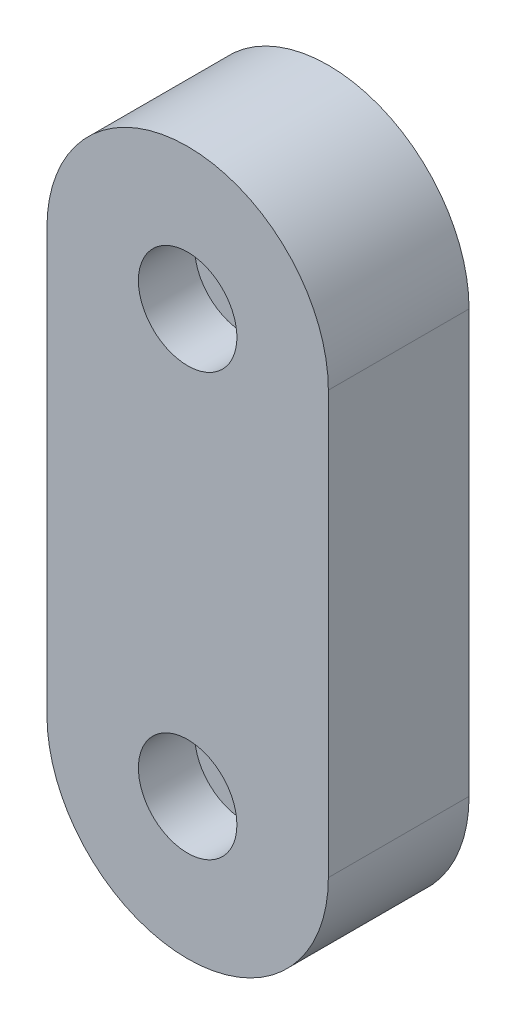
SolidWorks part; units mm, degrees
ref_plane "Front Plane" through (0, 0, 0) normal (0, 0, 1) x (1, 0, 0)
ref_plane "Top Plane" through (0, 0, 0) normal (0, 1, 0) x (1, 0, 0)
ref_plane "Right Plane" through (0, 0, 0) normal (1, 0, 0) x (0, 0, -1)
sketch "Sketch1" plane through (0, 0, 0) normal (0, 0, 1) x (1, 0, 0)
  line L0 (0, 0) -> (0, 30) construction
  line L1 (-10, 0) -> (-10, 30)
  line L2 (10, 0) -> (10, 30)
  arc A0 (-10, 0) -> (10, 0) centre (0, 0) ccw
  arc A1 (10, 30) -> (-10, 30) centre (0, 30) ccw
  point P3 (0, 15)
  dimension "D1" = 30
  dimension "D2" = 20
extrude "Boss-Extrude1" add sketch "Sketch1" along normal blind 10
sketch "Sketch3" plane through (0, 0, 10) normal (0, 0, 1) x (1, 0, 0)
  line L0 (10, 15) -> (-10, 15) construction
  line L1 (10, 0) -> (10, 30) construction
  line L2 (-10, 30) -> (-10, 0) construction
  circle A0 centre (0, 0) radius 3.5
  circle A1 centre (0, 30) radius 3.5
  dimension "D1" = 7
extrude "Cut-Extrude1" cut sketch "Sketch3" against normal blind 4
sketch "Sketch4" plane through (0, 0, 6) normal (0, 0, 1) x (1, 0, 0)
  line L0 (-10, 15) -> (10, 15) construction
  line L1 (-10, 30) -> (-10, 0) construction
  line L2 (10, 0) -> (10, 30) construction
  circle A0 centre (0, 0) radius 1.55
  circle A1 centre (0, 30) radius 1.55
  dimension "D1" = 3.1
extrude "Cut-Extrude2" cut sketch "Sketch4" against normal blind 22
